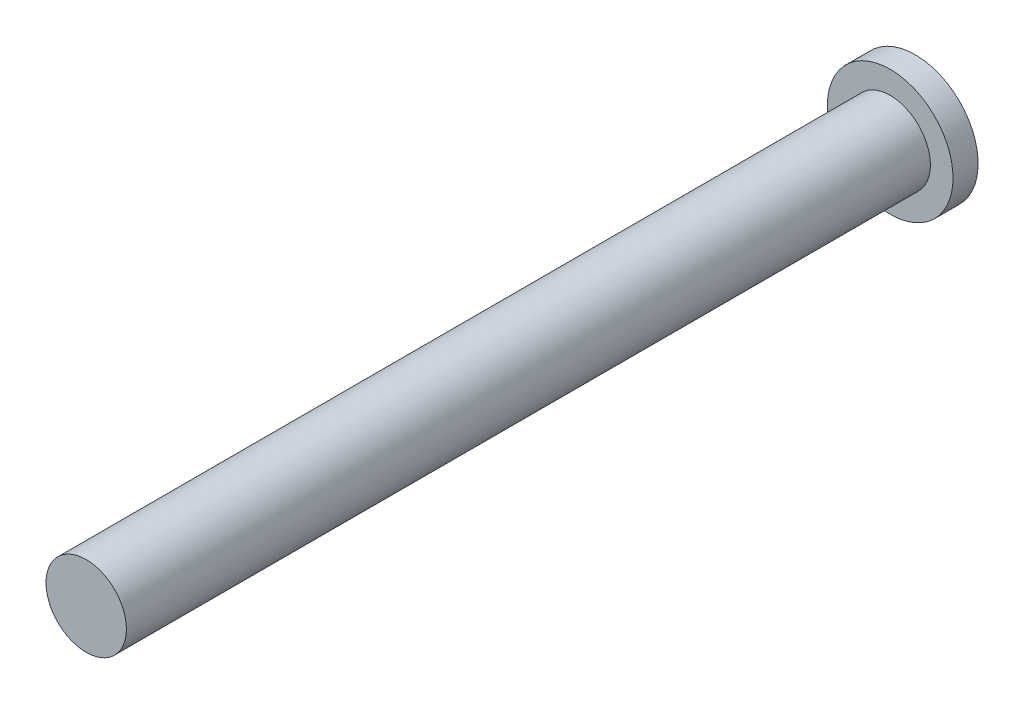
SolidWorks part; units mm, degrees
ref_plane "Front Plane" through (0, 0, 0) normal (0, 0, 1) x (1, 0, 0)
ref_plane "Top Plane" through (0, 0, 0) normal (0, 1, 0) x (1, 0, 0)
ref_plane "Right Plane" through (0, 0, 0) normal (1, 0, 0) x (0, 0, -1)
sketch "Sketch2" plane through (0, 0, 0) normal (0, 0, 1) x (1, 0, 0)
  circle A0 centre (0, 0) radius 1.6
  dimension "D1" = 3.2
extrude "Boss-Extrude1" add sketch "Sketch2" along normal blind 32
sketch "Sketch4" plane through (0, 0, 0) normal (0, 0, -1) x (-1, 0, 0)
  circle A0 centre (0, 0) radius 2.5
  dimension "D1" = 5
extrude "Boss-Extrude2" add sketch "Sketch4" along normal blind 1
